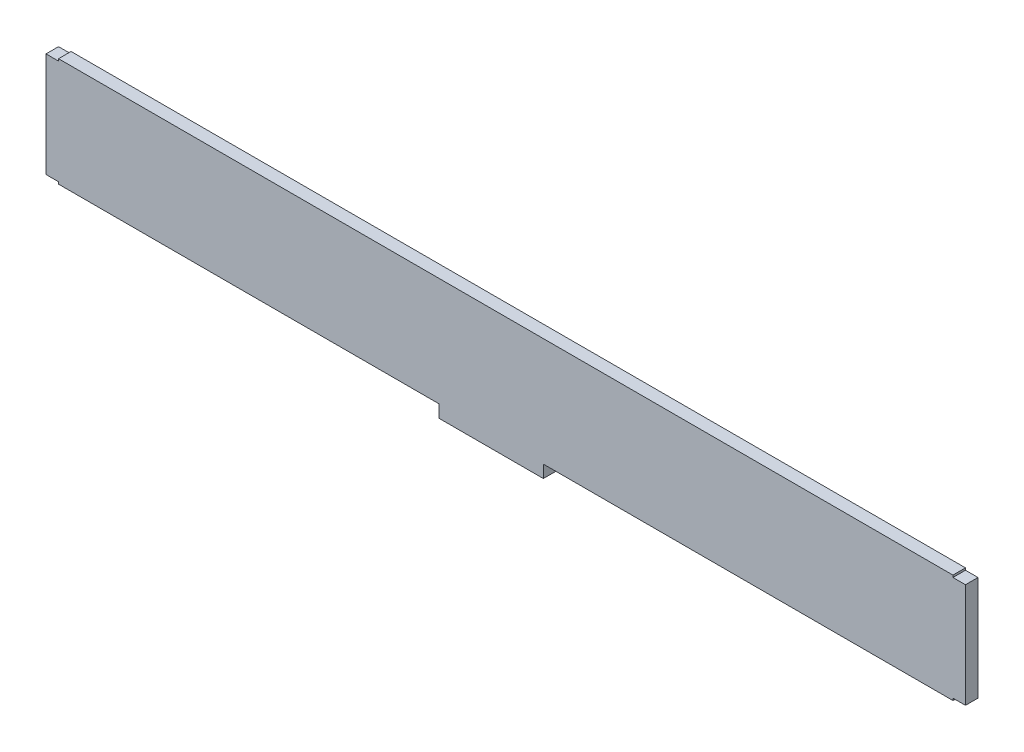
SolidWorks part; units mm, degrees
material "Maple"
ref_plane "Front Plane" through (0, 0, 0) normal (0, 0, 1) x (1, 0, 0)
ref_plane "Top Plane" through (0, 0, 0) normal (0, 1, 0) x (1, 0, 0)
ref_plane "Right Plane" through (0, 0, 0) normal (1, 0, 0) x (0, 0, -1)
sketch "Sketch1" plane through (0, 0, 0) normal (0, 0, 1) x (1, 0, 0)
  line L0 (214, 0) -> (214, -35) construction
  line L25 (0, 0) -> (428, 0)
  line L26 (0, 0) -> (0, -1)
  line L53 (0, -52) -> (182, -52)
  line L54 (428, 0) -> (428, -1)
  line L56 (182, -52) -> (182, -58)
  line L57 (182, -58) -> (232, -58)
  line L58 (232, -52) -> (232, -58)
  line L61 (428, -35) -> (214, -35) construction
  line L62 (0, -51) -> (0, -52)
  line L67 (434, -51) -> (428, -51)
  line L68 (434, -1) -> (434, -51)
  line L69 (-6, -1) -> (0, -1)
  line L70 (-6, -1) -> (-6, -51)
  line L71 (-6, -51) -> (0, -51)
  line L73 (-6, -1) -> (0, -35) construction
  line L74 (-6, -51) -> (0, -35) construction
  line L75 (434, -1) -> (428, -1)
  line L76 (428, -51) -> (428, -52)
  line L77 (232, -52) -> (428, -52)
  line L78 (214, -53) -> (214, -70) construction
  point P5 (214, -70)
  point P14 (27, -35)
  dimension "D1" = 428
  dimension "D2" = 52
  dimension "D3" = 50
  dimension "D4" = 1
  dimension "D5" = 1
  dimension "D6" = 182
  dimension "D7" = 50
  dimension "D8" = 50
  dimension "D9" = 6
  dimension "D10" = 6
  dimension "D11" = 6
extrude "Boss-Extrude1" add sketch "Sketch1" along normal blind 6
